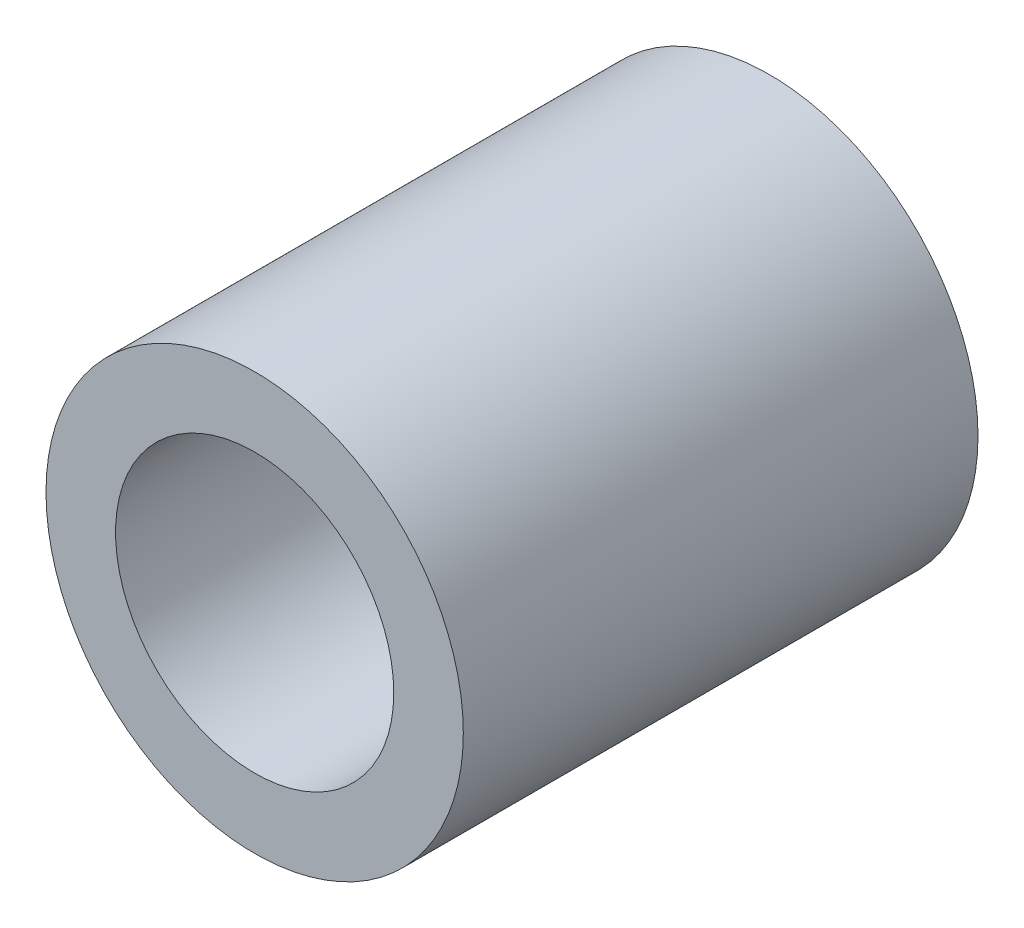
SolidWorks part; units mm, degrees
ref_plane "Front Plane" through (0, 0, 0) normal (0, 0, 1) x (1, 0, 0)
ref_plane "Top Plane" through (0, 0, 0) normal (0, 1, 0) x (1, 0, 0)
ref_plane "Right Plane" through (0, 0, 0) normal (1, 0, 0) x (0, 0, -1)
sketch "Sketch1" plane through (0, 0, 0) normal (0, 0, 1) x (1, 0, 0)
  circle A0 centre (0, 0) radius 2.3813
  circle A1 centre (0, 0) radius 1.5875
  dimension "D1" = 4.7625
  dimension "D2" = 3.175
extrude "Boss-Extrude1" add sketch "Sketch1" along normal blind 5.8738
